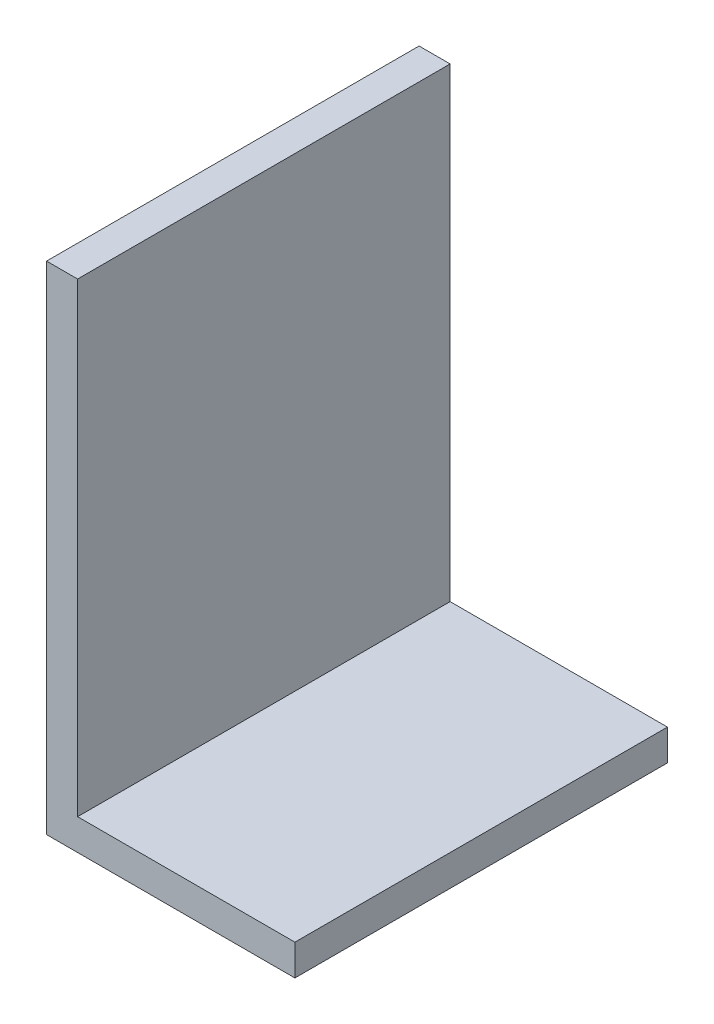
SolidWorks part; units mm, degrees
ref_plane "Front Plane" through (0, 0, 0) normal (0, 0, 1) x (1, 0, 0)
ref_plane "Top Plane" through (0, 0, 0) normal (0, 1, 0) x (1, 0, 0)
ref_plane "Right Plane" through (0, 0, 0) normal (1, 0, 0) x (0, 0, -1)
sketch "Sketch1" plane through (0, 0, 0) normal (0, 0, 1) x (1, 0, 0)
  line L0 (-9.525, -22.225) -> (12.7, -22.225)
  line L1 (-12.7, -25.4) -> (12.7, -25.4)
  line L2 (-12.7, -25.4) -> (-12.7, 25.4)
  line L3 (-9.525, -22.225) -> (-9.525, 25.4)
  line L4 (12.7, -25.4) -> (12.7, -22.225)
  line L5 (-12.7, 25.4) -> (-9.525, 25.4)
  dimension "D1" = 50.8
  dimension "D2" = 25.4
  dimension "D3" = 3.175
extrude "Boss-Extrude1" add sketch "Sketch1" along normal blind 38.1
